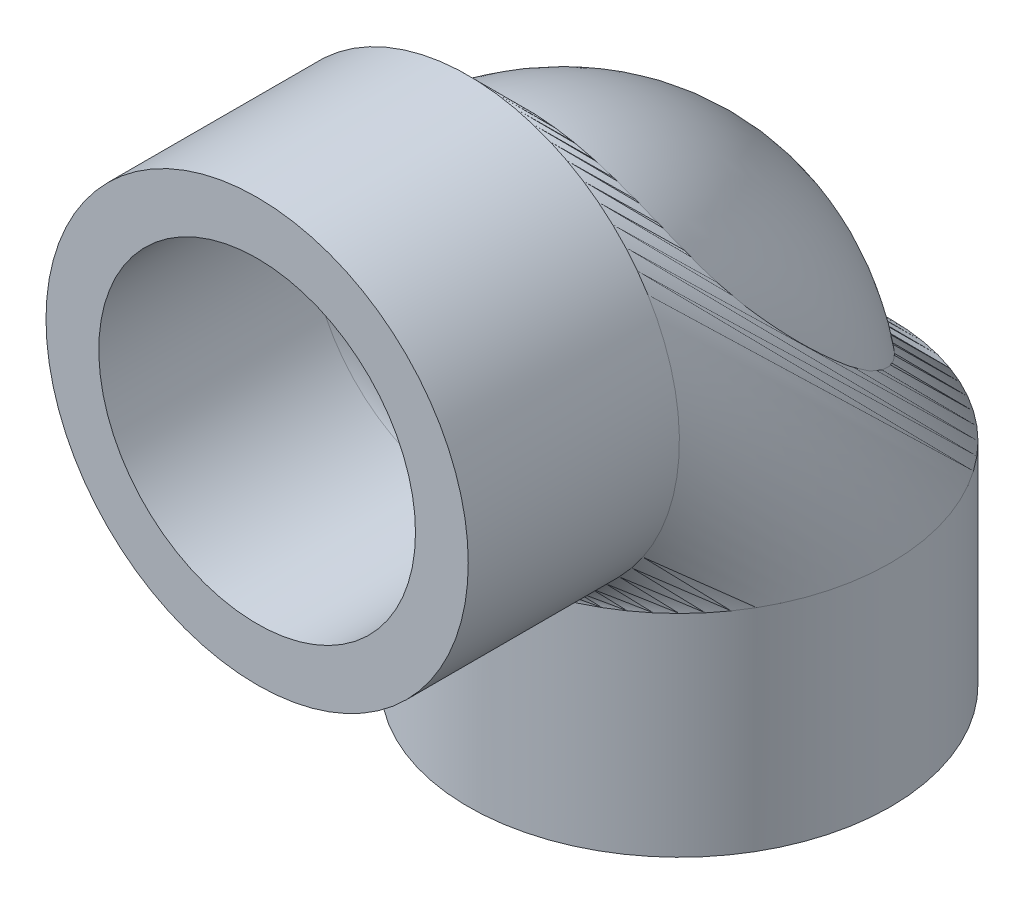
SolidWorks part; units mm, degrees
ref_plane "前视基准面" through (0, 0, 0) normal (0, 0, 1) x (1, 0, 0)
ref_plane "上视基准面" through (0, 0, 0) normal (0, 1, 0) x (1, 0, 0)
ref_plane "右视基准面" through (0, 0, 0) normal (1, 0, 0) x (0, 0, -1)
sketch "草图1" plane through (0, 0, 0) normal (0, 0, 1) x (1, 0, 0)
  circle A0 centre (0, 0) radius 10
  dimension "D1" = 20
sketch "草图2" plane through (0, 0, 0) normal (1, 0, 0) x (0, 0, -1)
  line L0 (0, 0) -> (10, 0)
  line L1 (20, -10) -> (20, -20)
  arc A0 (10, 0) -> (20, -10) centre (10, -10) cw
  dimension "D1" = 10
  dimension "D2" = 10
sweep "扫描1" add profiles "草图1" path "草图2"
sketch "草图3" plane through (0, 0, 0) normal (0, 0, 1) x (1, 0, 0)
  circle A0 centre (0, 0) radius 7.5
  dimension "D1" = 15
sketch "草图4" plane through (0, 0, 0) normal (1, 0, 0) x (0, 0, -1)
  line L0 (0, 0) -> (10, 0)
  line L1 (20, -10) -> (20, -20)
  line L2 (10, -20) -> (30, -20) construction
  arc A0 (20, -10) -> (10, 0) centre (10, -10) ccw
  dimension "D1" = 10
sweep "切除-扫描1" cut profiles "草图3" path "草图4"
